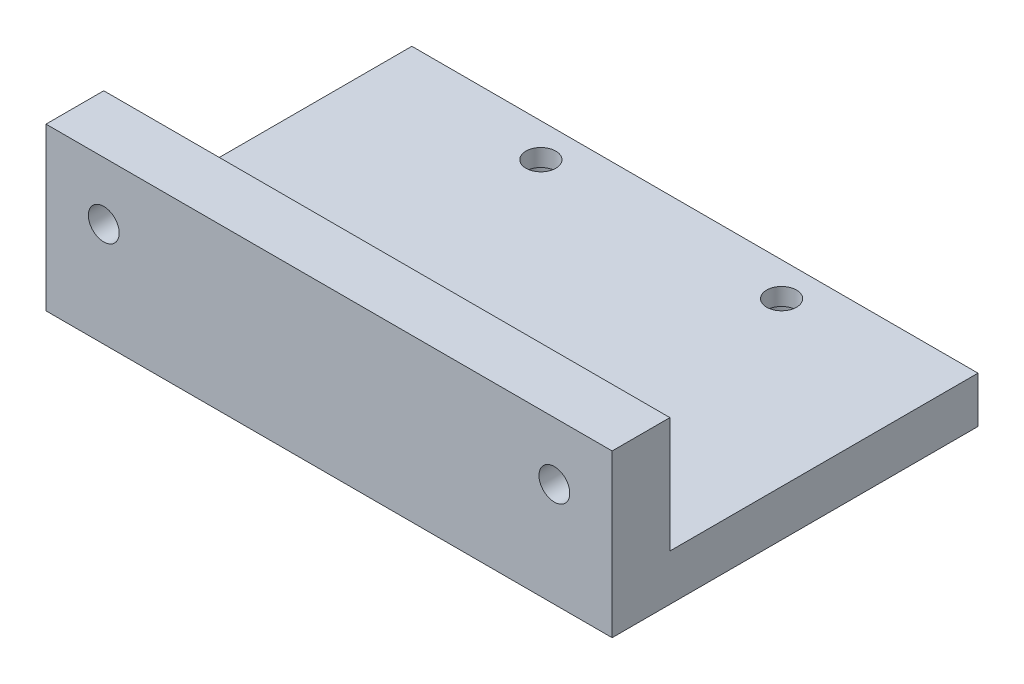
SolidWorks part; units mm, degrees
ref_plane "Front Plane" through (0, 0, 0) normal (0, 0, 1) x (1, 0, 0)
ref_plane "Top Plane" through (0, 0, 0) normal (0, 1, 0) x (1, 0, 0)
ref_plane "Right Plane" through (0, 0, 0) normal (1, 0, 0) x (0, 0, -1)
sketch "Sketch1" plane through (0, 0, 0) normal (0, 1, 0) x (1, 0, 0)
  line L5 (-29.4, -16) -> (29.4, -16)
  line L6 (-29.4, -16) -> (-29.4, 16)
  line L7 (-29.4, 16) -> (29.4, 16)
  line L8 (29.4, -16) -> (29.4, 16)
  line L9 (-29.4, -16) -> (29.4, 16) construction
  line L10 (-29.4, 16) -> (29.4, -16) construction
  line L11 (-12.5, -12.5) -> (12.5, -12.5) construction
  line L12 (-12.5, -12.5) -> (-12.5, 12.5) construction
  line L13 (-12.5, 12.5) -> (12.5, 12.5) construction
  line L14 (12.5, -12.5) -> (12.5, 12.5) construction
  line L15 (-12.5, -12.5) -> (12.5, 12.5) construction
  line L16 (-12.5, 12.5) -> (12.5, -12.5) construction
  circle A0 centre (-12.5, 12.5) radius 1.55
  circle A1 centre (12.5, 12.5) radius 1.55
  circle A2 centre (12.5, -12.5) radius 1.55
  circle A3 centre (-12.5, -12.5) radius 1.55
  point P0 (0, 0)
  point P7 (0, 0)
  dimension "D5" = 3.1
  dimension "D1" = 25
  dimension "D2" = 25
  dimension "D3" = 58.8
  dimension "D4" = 32
extrude "Boss-Extrude1" add sketch "Sketch1" along normal blind 4.8
sketch "Sketch2" plane through (0, 0, 0) normal (0, -1, 0) x (1, 0, 0)
  circle A0 centre (-12.5, 12.5) radius 3
  circle A1 centre (12.5, 12.5) radius 3
  circle A2 centre (12.5, -12.5) radius 3
  circle A3 centre (-12.5, -12.5) radius 3
  dimension "D1" = 6
extrude "Cut-Extrude1" cut sketch "Sketch2" against normal blind 3 contours A3
sketch "Sketch3" plane through (0, 0, 0) normal (0, -1, 0) x (1, 0, 0)
  line L1 (-29.4, 16) -> (29.4, 16)
  line L2 (-29.4, 16) -> (-29.4, 22)
  line L3 (-29.4, 22) -> (29.4, 22)
  line L4 (29.4, 16) -> (29.4, 22)
  dimension "D1" = 6
extrude "Boss-Extrude2" add sketch "Sketch3" against normal offset from surface (16.8 mm away) 12 up to face at (0, 4.8, 0) offset beyond the face yes
sketch "Sketch4" plane through (0, 0, 16) normal (0, 0, -1) x (-1, 0, 0)
  line L0 (0, 4.8) -> (0, 16.8) construction
  line L1 (-20.1668, 10.8) -> (-21.7834, 13.6)
  line L2 (-21.7834, 13.6) -> (-25.0166, 13.6)
  line L3 (-25.0166, 13.6) -> (-26.6332, 10.8)
  line L4 (-26.6332, 10.8) -> (-25.0166, 8)
  line L5 (-25.0166, 8) -> (-21.7834, 8)
  line L6 (-21.7834, 8) -> (-20.1668, 10.8)
  line L7 (29.4, 4.8) -> (-29.4, 4.8) construction
  line L8 (-29.4, 16.8) -> (29.4, 16.8) construction
  line L9 (-23.4, 10.8) -> (0, 10.8) construction
  line L10 (-29.4, 16.8) -> (-29.4, 4.8) construction
  circle A0 centre (-23.4, 10.8) radius 2.8 construction
  dimension "D1" = 5.6
  dimension "D2" = 6
extrude "Cut-Extrude2" cut sketch "Sketch4" against normal blind 3
sketch "Sketch5" plane through (0, 0, 19) normal (0, 0, -1) x (-1, 0, 0)
  line L0 (-20.1668, 10.8) -> (-26.6332, 10.8) construction
  circle A0 centre (-23.4, 10.8) radius 1.6
  dimension "D1" = 3.2
extrude "Cut-Extrude3" cut sketch "Sketch5" against normal through all
mirror "Mirror1" about plane through (0, 0, 0) normal (1, 0, 0) of "Cut-Extrude2", "Cut-Extrude3"
